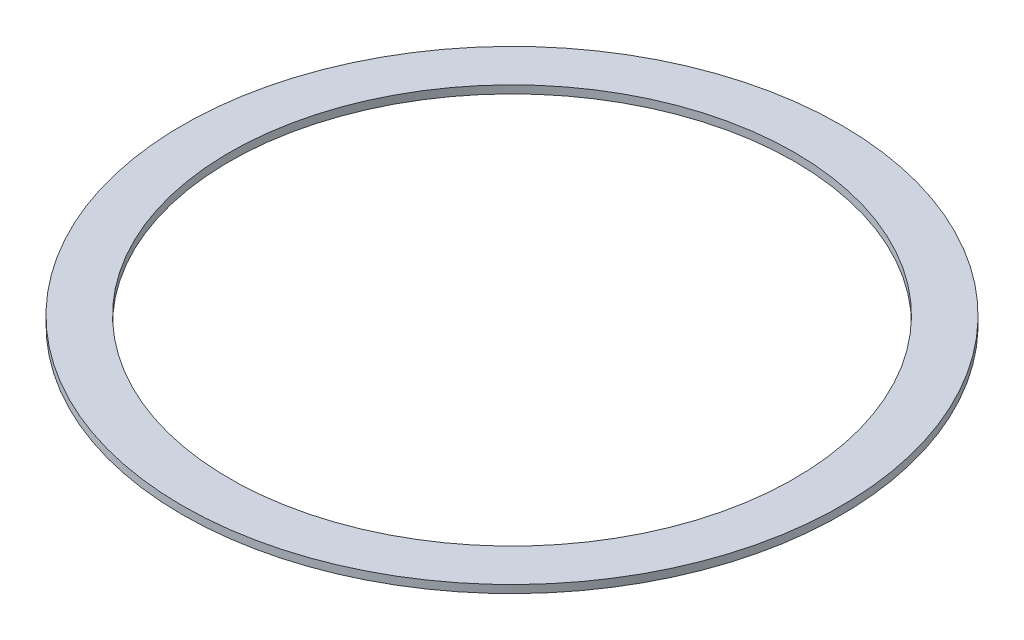
SolidWorks part; units mm, degrees
ref_plane "Plano frontal" through (0, 0, 0) normal (0, 0, 1) x (1, 0, 0)
ref_plane "Plano superior" through (0, 0, 0) normal (0, 1, 0) x (1, 0, 0)
ref_plane "Plano direito" through (0, 0, 0) normal (1, 0, 0) x (0, 0, -1)
sketch "Esboço1" plane through (0, 0, 0) normal (0, 0, 1) x (1, 0, 0)
  line L0 (-28.6264, -36.0398) -> (-28.6264, 32.1244) construction
  line L2 (16.3736, -2.3985) -> (23.8736, -2.3985)
  line L3 (16.3736, -2.3985) -> (16.3736, -3.6485)
  line L4 (16.3736, -3.6485) -> (23.8736, -3.6485)
  line L5 (23.8736, -2.3985) -> (23.8736, -3.6485)
  line L6 (16.3736, -2.3985) -> (23.8736, -3.6485) construction
  line L7 (16.3736, -3.6485) -> (23.8736, -2.3985) construction
  point P2 (20.1236, -3.0235)
  dimension "D1" = 1.25
  dimension "D2" = 45
  dimension "D3" = 52.5
revolve "Revolução1" add sketch "Esboço1" angle 360 about L0
